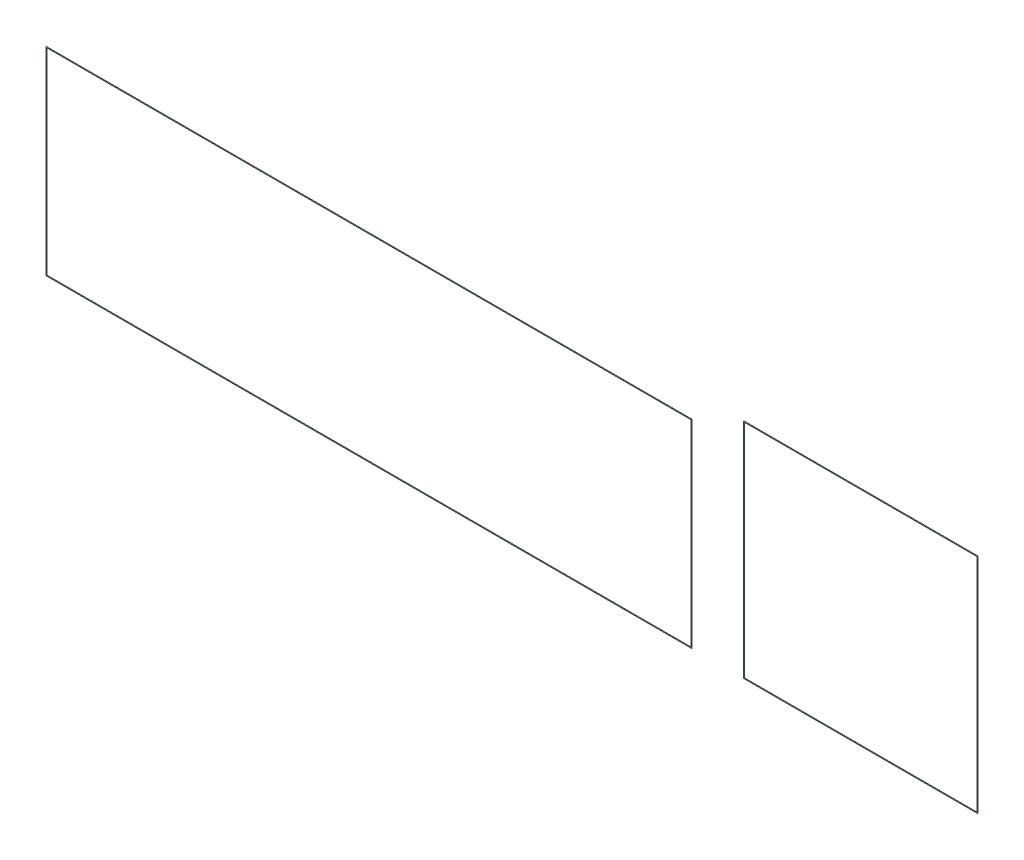
SolidWorks part; units mm, degrees
ref_plane "Alzado" through (0, 0, 0) normal (0, 0, 1) x (1, 0, 0)
ref_plane "Planta" through (0, 0, 0) normal (0, 1, 0) x (1, 0, 0)
ref_plane "Vista lateral" through (0, 0, 0) normal (1, 0, 0) x (0, 0, -1)
sketch "Croquis1" plane through (0, 0, 0) normal (0, 0, 1) x (1, 0, 0)
  line L0 (-31291.415, 9560) -> (-31291.415, -9560)
  line L1 (-31391.415, 9660) -> (31391.415, 9660)
  line L2 (-31391.415, 9660) -> (-31391.415, -9660)
  line L3 (-31391.415, -9660) -> (31391.415, -9660)
  line L4 (31391.415, 9660) -> (31391.415, -9660)
  line L5 (-31391.415, 9660) -> (31391.415, -9660) construction
  line L6 (-31391.415, -9660) -> (31391.415, 9660) construction
  line L7 (-31291.415, -9560) -> (31291.415, -9560)
  line L8 (31291.415, 9560) -> (31291.415, -9560)
  line L9 (-31291.415, 9560) -> (31291.415, 9560)
  point P0 (0, 0)
  dimension "D1" = 62782.83
  dimension "D2" = 19320
  dimension "D3" = 100
extrude "Saliente-Extruir1" add sketch "Croquis1" along normal blind 1
sketch "Croquis3" plane through (0, 0, 0) normal (0, 0, 1) x (1, 0, 0)
  line L0 (36391.415, 12040) -> (36491.415, 12040) construction
  line L1 (36491.415, 11940) -> (36491.415, -9560)
  line L2 (31291.415, 9560) -> (31391.415, 9560) construction
  line L3 (31391.415, -9660) -> (31391.415, 9660) construction
  line L4 (36391.415, 11940) -> (36491.415, 11940) construction
  line L5 (36491.415, 11940) -> (59091.415, 11940)
  line L6 (59091.415, 11940) -> (59091.415, -9560)
  line L7 (59091.415, -9560) -> (36491.415, -9560)
  line L8 (59191.415, 12040) -> (59191.415, -9660)
  line L9 (59191.415, -9660) -> (36391.415, -9660)
  line L10 (36391.415, 12040) -> (36391.415, -9660)
  line L11 (36391.415, 12040) -> (59191.415, 12040)
  line L12 (31391.415, -9660) -> (36391.415, -9660) construction
  dimension "D1" = 5000
  dimension "D2" = 22600
  dimension "D3" = 21500
  dimension "D4" = 100
extrude "Saliente-Extruir2" add sketch "Croquis3" along normal blind 1 separate body
